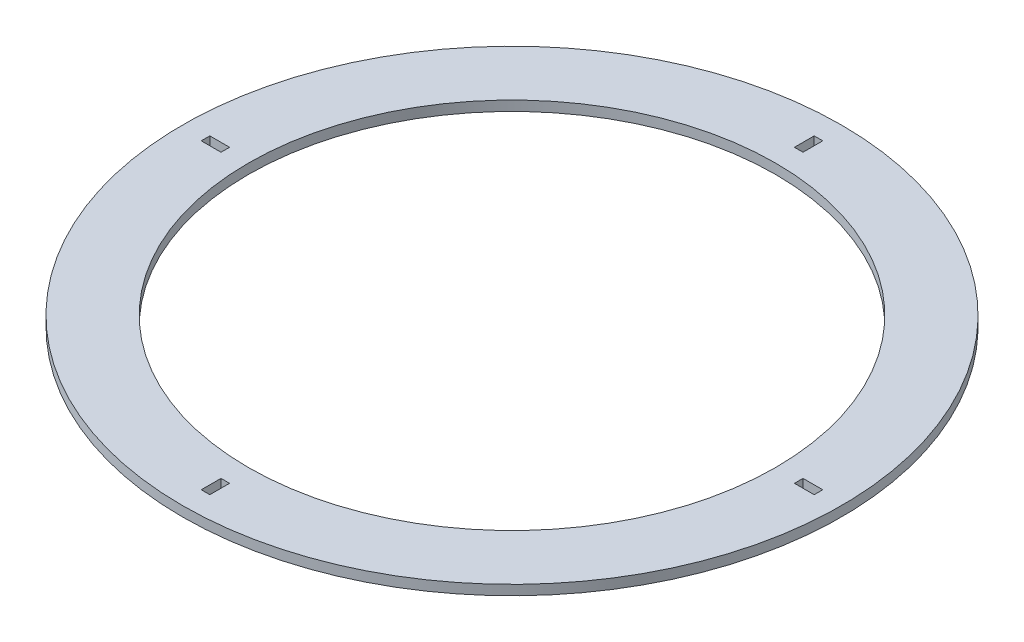
SolidWorks part; units mm, degrees
ref_plane "Front Plane" through (0, 0, 0) normal (0, 0, 1) x (1, 0, 0)
ref_plane "Top Plane" through (0, 0, 0) normal (0, 1, 0) x (1, 0, 0)
ref_plane "Right Plane" through (0, 0, 0) normal (1, 0, 0) x (0, 0, -1)
ref_plane "Base Height Plane" through (0, 0, 0) normal (0, 1, 0) x (1, 0, 0)
sketch "Sketch2" plane through (0, 0, 0) normal (0, 1, 0) x (1, 0, 0)
  line L0 (0, -80) -> (0, -100) construction
  circle A0 centre (0, 0) radius 100
  circle A1 centre (0, 0) radius 80
  point P7 (0, -90)
  dimension "D1" = 200
  dimension "D2" = 20
extrude "Boss-Extrude1" add sketch "Sketch2" along normal blind 3
sketch "Sketch3" plane through (0, 3, 0) normal (0, 1, 0) x (1, 0, 0)
  line L1 (1.3, -93) -> (-1.3, -93)
  line L2 (1.3, -93) -> (1.3, -87)
  line L3 (1.3, -87) -> (-1.3, -87)
  line L4 (-1.3, -93) -> (-1.3, -87)
  line L5 (0, -87) -> (0, -93) construction
  line L6 (1.3, -90) -> (-1.3, -90) construction
  point P0 (0, -90)
  point P4 (0, -92.8018)
  point P5 (0, -93)
  point P6 (0, 0)
  dimension "D2" = 2.6
extrude "Cut-Extrude1" cut sketch "Sketch3" against normal through all
pattern_circular "CirPattern1" count 4 over 360 about axis through (0, 0, 0) along (0, 1, 0) of "Cut-Extrude1"
